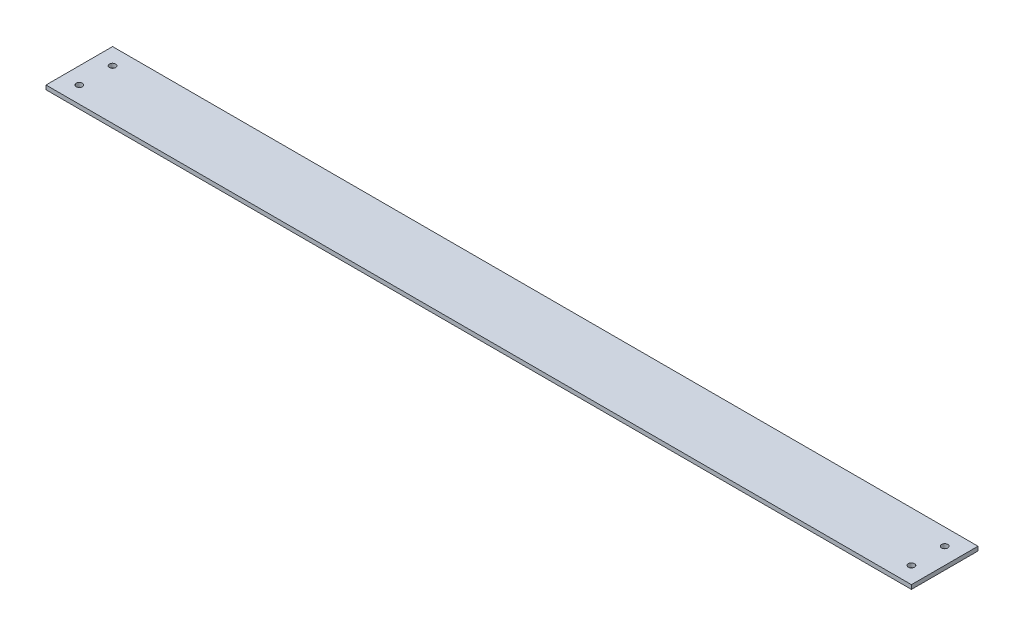
SolidWorks part; units mm, degrees
ref_plane "Front Plane" through (0, 0, 0) normal (0, 0, 1) x (1, 0, 0)
ref_plane "Top Plane" through (0, 0, 0) normal (0, 1, 0) x (1, 0, 0)
ref_plane "Right Plane" through (0, 0, 0) normal (1, 0, 0) x (0, 0, -1)
sketch "Sketch1" plane through (0, 0, 0) normal (0, 1, 0) x (1, 0, 0)
  line L0 (0, 25.4) -> (0, -25.4) construction
  line L1 (-330.2, 25.4) -> (330.2, 25.4)
  line L2 (-330.2, 25.4) -> (-330.2, -25.4)
  line L3 (-330.2, -25.4) -> (330.2, -25.4)
  line L4 (330.2, 25.4) -> (330.2, -25.4)
  line L5 (-330.2, 25.4) -> (330.2, -25.4) construction
  line L6 (-330.2, -25.4) -> (330.2, 25.4) construction
  circle A0 centre (-317.5, 12.7) radius 2.3813
  circle A1 centre (-317.5, -12.7) radius 2.3813
  circle A2 centre (317.5, -12.7) radius 2.3813
  circle A3 centre (317.5, 12.7) radius 2.3813
  point P0 (0, 0)
  dimension "D3" = 4.7625
  dimension "D4" = 4.7625
  dimension "D1" = 50.8
  dimension "D2" = 660.4
  dimension "D5" = 12.7
  dimension "D6" = 12.7
  dimension "D7" = 12.7
  dimension "D8" = 12.7
extrude "Boss-Extrude1" add sketch "Sketch1" along normal blind 3.175
